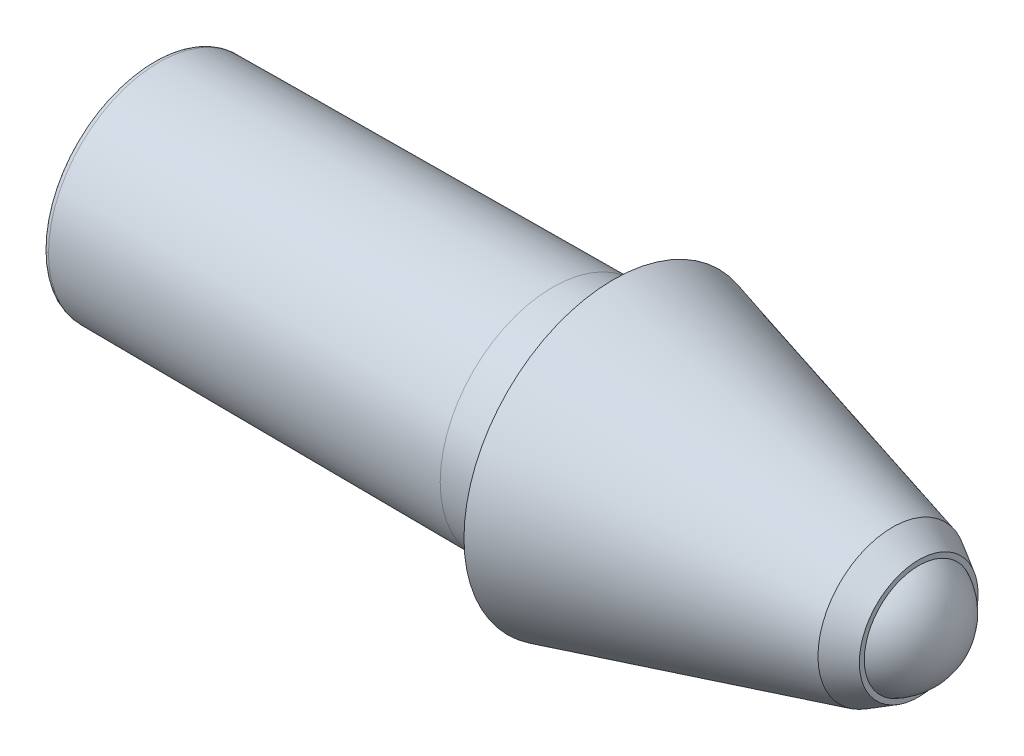
SolidWorks part; units mm, degrees
material "Brass"
ref_plane "Frontal" through (0, 0, 0) normal (0, 0, 1) x (1, 0, 0)
ref_plane "Superior" through (0, 0, 0) normal (0, 1, 0) x (1, 0, 0)
ref_plane "Lateral" through (0, 0, 0) normal (1, 0, 0) x (0, 0, -1)
sketch "Sketch1" plane through (0, 0, 0) normal (0, 0, 1) x (1, 0, 0)
  line L0 (-2, 0) -> (7.191, 0) construction
  line L1 (0, 0.45) -> (0, 0.8603)
  line L2 (0.05, 0.9103) -> (3.3, 0.9282)
  line L3 (4.3, 1.1472) -> (4.3, 1.0759) construction
  line L4 (3.7, 0.45) -> (0, 0.45)
  line L5 (6.1035, 0.615) -> (3.8, 1.2322)
  line L6 (4.05, 1.3396) -> (4.05, 0.8) construction
  line L7 (5.6429, 0.25) -> (5.8929, 0.5)
  line L8 (6.32, 0.49) -> (6.1035, 0.615)
  line L9 (3.7, 0.45) -> (3.7289, 0.4)
  line L10 (5.0866, 0.25) -> (5.6429, 0.25)
  line L11 (6.1, 0.5) -> (5.8929, 0.5)
  line L12 (3.3, 0.9282) -> (3.8, 0.9282)
  line L13 (3.7289, 0.4) -> (5, 0.4)
  line L14 (5, 0.4) -> (5.0866, 0.25)
  line L15 (3.8, 1.15) -> (3.3356, 1.0107) construction
  line L16 (3.8, 0.9282) -> (3.8, 1.15)
  line L17 (3.3, 0.9628) -> (3.3, 0.9282) construction
  line L18 (6.32, 0.49) -> (6.32, 0.449)
  line L19 (3.8, 1.15) -> (3.8, 1.2322)
  arc A0 (0.0497, 0.9103) -> (0, 0.8603) centre (0.05, 0.8603) ccw construction
  arc A1 (3.3, 0.9628) -> (3.3356, 1.0107) centre (3.35, 0.9628) cw construction
  arc A2 (6.1, 0.5) -> (6.32, 0.449) centre (6.1, 0) cw
  circle A3 centre (6.1, 0) radius 0.5 construction
  arc A8 (0.05, 0.9103) -> (0, 0.8603) centre (0.05, 0.8603) ccw
  point P17 (3.3, 1)
  dimension "D3" = 2
  dimension "D11" = 6.6
  dimension "D21" = 30
  dimension "D16" = 0.98
  dimension "D4" = 2.3
  dimension "D6" = 0.05
  dimension "D7" = 0.2165
  dimension "D25" = 2.4644
  dimension "D9" = 15
  dimension "D15" = 1
  dimension "D28" = 0.28
  dimension "D5" = 0.5
  dimension "D8" = 0.9
  dimension "D10" = 45
  dimension "D12" = 1.8206
  dimension "D13" = 1.23
  dimension "D14" = 60
  dimension "D17" = 0.5
  dimension "D18" = 0.8
  dimension "D19" = 5
  dimension "D20" = 0.317
  dimension "D22" = 0.898
  dimension "D23" = 1.8565
  dimension "D24" = 3.3
  dimension "D26" = 0.5
revolve "Base-Revolve" add sketch "Sketch1" angle 360 about L0
sketch "Sketch2" plane through (0, 0, 0) normal (0, 0, 1) x (1, 0, 0)
  line L0 (4.4284, 0) -> (7.1275, 0) construction
  line L1 (-2, 0) -> (7.191, 0) construction
  line L3 (5.6, 0) -> (6.6, 0)
  line L4 (6.32, -0.49) -> (6.32, 0.49) construction
  arc A0 (6.6, 0) -> (5.6, 0) centre (6.1, 0) ccw
  dimension "D1" = 0.28
  dimension "D2" = 1
revolve "Revolução3" add sketch "Sketch2" angle 360 about L0
